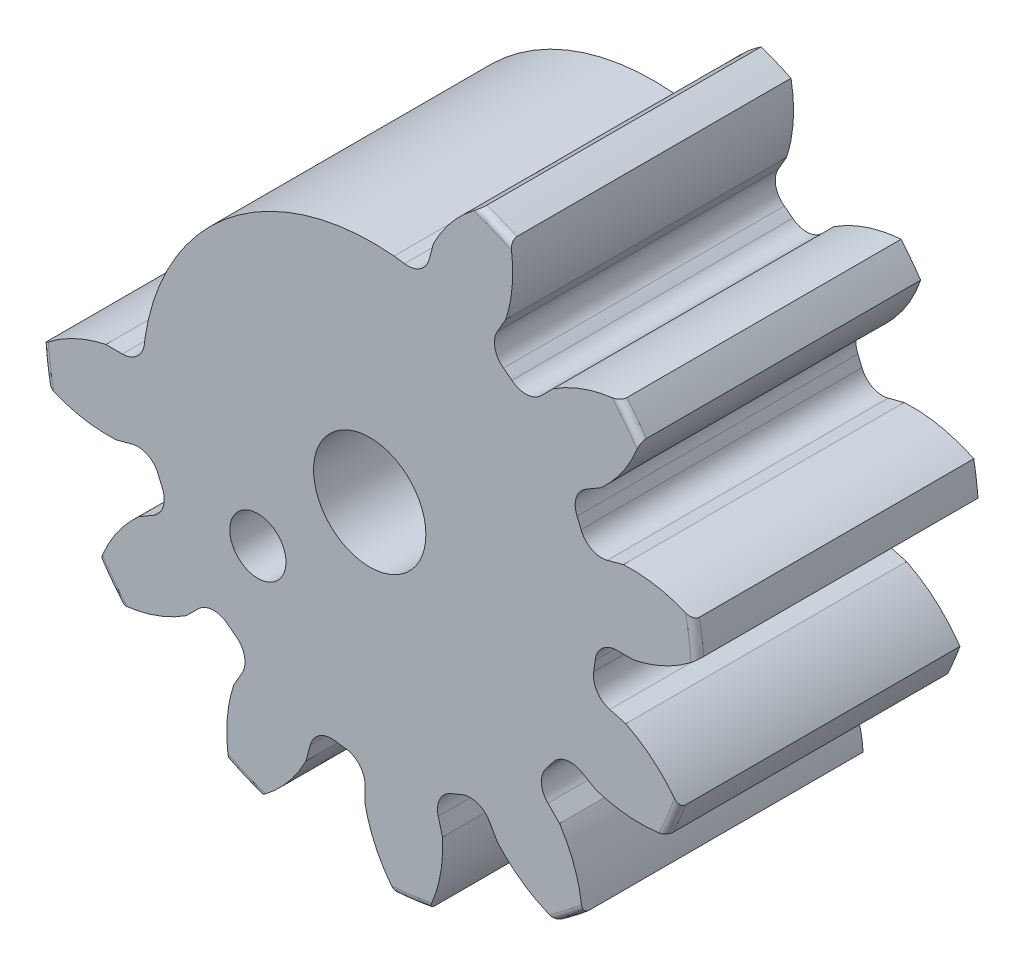
SolidWorks part; units mm, degrees
ref_plane "Front" through (0, 0, 0) normal (0, 0, 1) x (1, 0, 0)
ref_plane "Top" through (0, 0, 0) normal (0, 1, 0) x (1, 0, 0)
ref_plane "Right" through (0, 0, 0) normal (1, 0, 0) x (0, 0, -1)
sketch "Sketch1" plane through (0, 0, 0) normal (0, 0, 1) x (1, 0, 0)
  line L0 (-152.4, 0) -> (152.4, 0) construction
  circle A0 centre (0, 0) radius 14.859
  circle A1 centre (0, 0) radius 12.7 construction
  circle A3 centre (0, 0) radius 10.251 construction
  dimension "D1" = 2.449
  dimension "D2" = 4.608
  dimension "D3" = 2.159
extrude "Boss-Extrude1" add sketch "Sketch1" against normal blind 25.4
sketch "Sketch2" plane through (0, 0, 0) normal (1, 0, 0) x (0, 0, -1)
  line L0 (25.4, 0) -> (41.148, 0)
  line L1 (25.4, 0) -> (25.4, 9.525)
  line L2 (25.4, 9.525) -> (41.148, 9.525)
  line L3 (41.148, 9.525) -> (41.148, 0)
  point P5 (41.148, -9.525)
  point P6 (0, -14.859)
  point P7 (25.4, -14.859)
  point P9 (0, 14.859)
revolve "Revolve1" add sketch "Sketch2" angle 360 mid plane about L0
fillet "Fillet2" radius 0.2972 3 edges at (14.859, 0, -25.4) (14.859, 0, 0) (9.525, 0, -25.4)
sketch "Sketch3" plane through (0, 0, 0) normal (0, 0, 1) x (1, 0, 0)
  line L0 (0, 0) -> (0, 14.859) construction
  line L1 (-4.0817, 11.2144) -> (0, 12.7)
  line L2 (-9.5921, 12.7) -> (9.5921, 12.7) construction
  line L3 (-9.0136, 9.4193) -> (9.0136, 15.9807) construction
  line L4 (-4.0817, 11.2144) -> (0, 0) construction
  line L5 (-9.951, 6.5878) -> (0, 0) construction
  line L6 (-9.951, 6.5878) -> (-3.3571, 16.548) construction
  line L7 (-2.8353, 11.5924) -> (0, 0) construction
  line L8 (-2.8353, 11.5924) -> (0.1182, 12.3148) construction
  arc A0 (-4.0817, 11.2144) -> (-9.951, 6.5878) centre (0, 0) ccw
  circle A1 centre (0, 0) radius 12.7 construction
  circle A2 centre (0, 0) radius 11.9341 construction
  arc A3 (-4.0817, 11.2144) -> (-2.8353, 11.5924) centre (0, 0) cw
  circle A4 centre (0, 0) radius 14.859 construction
  point P6 (0, 12.7)
  dimension "D1" = 4.3437
  dimension "D3" = 11.9451
  dimension "D5" = 3.0406
  dimension "D2" = 7.6014
  dimension "D4" = 1.3031
sketch "Sketch4" plane through (0, 0, 0) normal (0, 0, 1) x (1, 0, 0)
  line L0 (0, 0) -> (1.6435, 12.4836) construction
  line L1 (0.2108, 11.9322) -> (0.2108, 10.2488)
  line L2 (0, 12.7) -> (3.287, 12.2673) construction
  line L3 (2.8847, 11.5802) -> (2.449, 9.9542)
  line L4 (0.2108, 10.2488) -> (0, 0) construction
  line L5 (0, 0) -> (0, 14.859) construction
  line L6 (-9.951, 6.5878) -> (-3.3571, 16.548) construction
  line L7 (-9.951, 6.5878) -> (-3.3571, 16.548) construction
  arc A0 (2.449, 9.9542) -> (0.2108, 10.2488) centre (0, 0) ccw
  arc A1 (0, 12.7) -> (3.287, 12.2673) centre (0, 0) cw construction
  circle A2 centre (0, 0) radius 12.7 construction
  circle A3 centre (0, 0) radius 11.9341 construction
  circle A4 centre (0, 0) radius 10.251 construction
  arc A5 (7.5257, 15.1152) -> (-3.3571, 16.548) centre (0, 0) ccw
  spline S0 degree 2 poles (-3.3571, 16.548) (-0.4015, 14.8243) (0.2108, 11.9322) knots 0 0 0 1 1 1
  spline S1 degree 2 poles (7.5257, 15.1152) (4.2246, 14.2152) (2.8847, 11.5802) knots 0 0 0 1 1 1
  dimension "D1" = 3.3249
extrude "Cut-Extrude1" cut sketch "Sketch4" against normal through all
fillet "Fillet1" radius 0.9975 2 edges at (2.449, 9.9542, -12.7) (0.2108, 10.2488, -12.7)
pattern_circular "CirPattern1" count 12 over 360 about axis through (0, 0, -25.4) along (0, 0, 1) of "Cut-Extrude1", "Fillet1"
sketch "Sketch5" plane through (0, 0, 0) normal (0, 0, 1) x (1, 0, 0)
  circle A0 centre (0, 0) radius 6.35
  circle A1 centre (0, 0) radius 6.35 construction
  dimension "Bore Min" = 12.7
  dimension "Bore Max" = 12.7
extrude "Cut-Extrude2" cut sketch "Sketch5" against normal through all
chamfer "Chamfer1" distance 0.4763 angle 45 3 edges at (9.525, 0, -41.148) (6.35, 0, 0) (6.35, 0, -41.148)
sketch "Pitch Dia" plane through (0, 0, 0) normal (0, 0, 1) x (1, 0, 0)
  circle A0 centre (0, 0) radius 12.7 construction
  circle A1 centre (0, 0) radius 12.7 construction
sketch "Sketch6" plane through (0, 0, -41.148) normal (0, 0, -1) x (-1, 0, 0)
  circle A0 centre (0, 0) radius 15.24
extrude "Cut-Extrude3" cut sketch "Sketch6" against normal blind 28.448
sketch "Sketch7" plane through (0, 0, 0) normal (0, 0, 1) x (1, 0, 0)
  circle A0 centre (0, 0) radius 6.8262
extrude "Boss-Extrude2" add sketch "Sketch7" against normal up to surface (12.7 mm away) up to face at (-6.35, 0, -12.7)
sketch "Sketch8" plane through (0, 0, 0) normal (0, 0, 1) x (1, 0, 0)
  circle A0 centre (0, 0) radius 2.54
extrude "Cut-Extrude4" cut sketch "Sketch8" against normal up to surface (12.7 mm away) up to face at (0, 0, -12.7)
sketch "Sketch9" plane through (0, 0, 0) normal (0, 0, 1) x (1, 0, 0)
  circle A0 centre (-5.0584, -4.2441) radius 1.27
extrude "Cut-Extrude5" cut sketch "Sketch9" against normal up to surface (12.7 mm away) up to face at (-2.54, 0, -12.7)
sketch "Sketch10" plane through (0, 0, 0) normal (0, 0, 1) x (1, 0, 0)
  line L0 (-17.8871, 2.4028) -> (-10.1633, 1.338)
  line L1 (1.2544, 18.0041) -> (1.1011, 10.1917)
  arc A0 (-10.1633, 1.338) -> (1.1011, 10.1917) centre (0.1398, -0.1778) cw
  arc A1 (-10.1294, 1.5742) -> (-10.1917, 1.1011) centre (0, 0) ccw construction
  arc A2 (-17.8871, 2.4028) -> (1.2544, 18.0041) centre (0, 0) cw
  arc A3 (0.2108, 11.1834) -> (1.1011, 10.1917) centre (1.2083, 11.1834) ccw construction
  point P11 (1.1011, 10.1917)
  point P14 (0, 0)
  point P15 (1.0513, 10.1984)
  point P19 (1.0878, 10.1932)
extrude "Cut-Extrude6" cut sketch "Sketch10" against normal up to surface (12.7 mm away) up to face at (-6.3284, -4.2441, -12.7)
equation "\"D1@Boss-Extrude1\" = \"Face Wd@Sketch2\""
equation "\"D2@Sketch3\" = \"D1@Sketch3\"*1.75"
equation "\"D3@Sketch3\" = \"D1@Sketch3\"+\"D2@Sketch3\""
equation "\"D4@Sketch3\" = \"D1@Sketch3\"*.3"
equation "\"D5@Sketch3\" = \"D1@Sketch3\"-\"D4@Sketch3\""
equation "\"D1@Sketch4\" = 1.5708/(\"Number of Teeth@Sketch1\"/\"Ptich Dia@Sketch1\")"
equation "\"D1@Chamfer1\" = \"B Hub Dia@Sketch2\"*.025"
equation "\"D1@CirPattern1\" = \"Number of Teeth@Sketch1\""
equation "\"D1@Fillet1\" = \"D1@Sketch4\"*.3"
equation "\"D1@Fillet2\" = \"OD@Sketch1\"*.01"
equation "\"D1@Sketch1\" = 1.157/(\"Number of Teeth@Sketch1\"/\"Ptich Dia@Sketch1\")"
